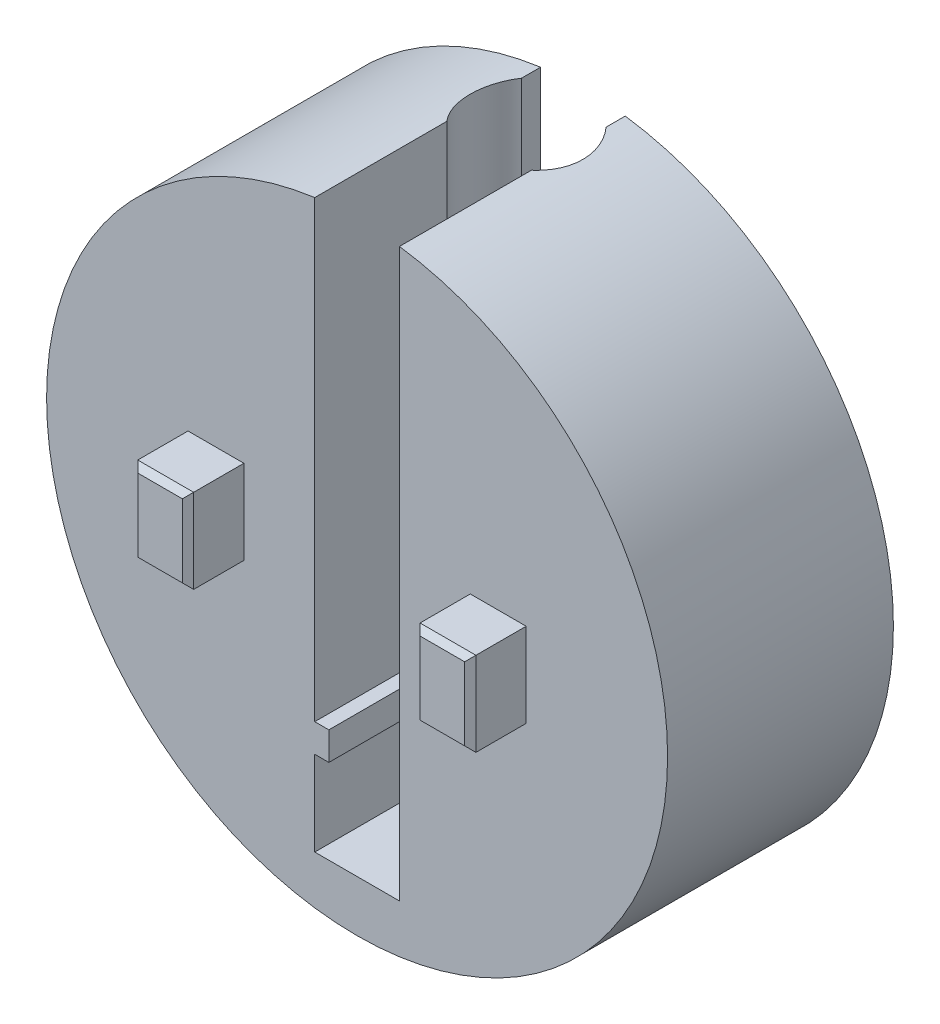
SolidWorks part; units mm, degrees
ref_plane "Front Plane" through (0, 0, 0) normal (0, 0, 1) x (1, 0, 0)
ref_plane "Top Plane" through (0, 0, 0) normal (0, 1, 0) x (1, 0, 0)
ref_plane "Right Plane" through (0, 0, 0) normal (1, 0, 0) x (0, 0, -1)
sketch "Sketch1" plane through (0, 0, 0) normal (0, 0, 1) x (1, 0, 0)
  line L0 (0, 0) -> (0, 11) construction
  line L1 (-1.5, 10.8972) -> (-1.5, -9.1833)
  line L2 (2, -5.1833) -> (-2, -5.1833)
  line L3 (2, -5.1833) -> (2, 10.8167)
  line L4 (2, 10.8167) -> (-2, 10.8167)
  line L5 (-2, -5.1833) -> (-2, 10.8167)
  line L6 (2, -5.1833) -> (-2, 10.8167) construction
  line L7 (2, 10.8167) -> (-2, -5.1833) construction
  line L8 (2, -5.1833) -> (-1, -5.1833)
  line L9 (2, -5.1833) -> (2, -6.1833)
  line L10 (2, -6.1833) -> (-1, -6.1833)
  line L11 (-1, -5.1833) -> (-1, -6.1833)
  line L12 (2, -6.1833) -> (-2, -6.1833)
  line L13 (2, -6.1833) -> (2, -9.1833)
  line L14 (2, -9.1833) -> (-2, -9.1833)
  line L15 (-2, -6.1833) -> (-2, -9.1833)
  line L16 (1.5, -9.1833) -> (1.5, 10.8972)
  circle A0 centre (0, 0) radius 11
  point P3 (0, 2.8167)
  dimension "D1" = 22
  dimension "D2" = 4
  dimension "D3" = 16
  dimension "D4" = 3
  dimension "D5" = 1
  dimension "D6" = 3
  dimension "D7" = 0.5
  dimension "D8" = 0.5
extrude "Boss-Extrude1" add sketch "Sketch1" along normal blind 8 contours L5 A0 L3 L9 L13 L14 L15 L12 L11 L2 | L12 L11 L2 L1 | L12 L15 L14 L1 | L5 L2 L1 L4 | L16 L2 L3 L4 | L16 L10 L9 L2 | L16 L14 L13 L10 | L4 A0 L16 | L1 A0 L4
sketch "Sketch8" plane through (0, 0, 0) normal (0, 1, 0) x (1, 0, 0)
  line L0 (-1.5, 0) -> (1.5, 0) construction
  line L1 (0, 0) -> (0, -2) construction
  circle A0 centre (0, -2) radius 2
  dimension "D1" = 4
sketch "Sketch4" plane through (0, 0, 0) normal (0, 0, -1) x (-1, 0, 0)
  line L0 (-2, 10.8167) -> (-2, -9.1833)
  line L1 (-2, -9.1833) -> (2, -9.1833)
  line L2 (2, -9.1833) -> (2, -6.1833)
  line L3 (2, -6.1833) -> (1, -6.1833)
  line L4 (1, -6.1833) -> (1, -5.1833)
  line L5 (1, -5.1833) -> (2, -5.1833)
  line L6 (2, -5.1833) -> (2, 10.8167)
  line L7 (-2, 10.8167) -> (2, 10.8167) construction
  line L8 (-1.5, 10.8972) -> (-1.5, -9.1833)
  line L9 (1.5, 10.8972) -> (1.5, -9.1833)
  circle A0 centre (0, 0) radius 11
  dimension "D1" = 22
  dimension "D2" = 0.5
  dimension "D3" = 0.5
  dimension "D4" = 20
  dimension "D5" = 4
  dimension "D6" = 0.5
extrude "pin hole" cut sketch "Sketch8" against normal up to surface (5.1833 mm away) and the other way through all up to face at (-1.25, -5.1833, 4)
sketch "Sketch6" plane through (0, 0, 0) normal (0, 0, -1) x (-1, 0, 0)
  line L0 (-11, 0) -> (11, 0) construction
  line L1 (-6, 1.5) -> (-4, -1.5) construction
  line L2 (-6, 1.5) -> (-4, 1.5)
  line L3 (-6, 1.5) -> (-6, -1.5)
  line L4 (-6, -1.5) -> (-4, -1.5)
  line L5 (-4, 1.5) -> (-4, -1.5)
  line L6 (4, 1.5) -> (6, 1.5)
  line L7 (4, 1.5) -> (4, -1.5)
  line L8 (4, -1.5) -> (6, -1.5)
  line L9 (6, 1.5) -> (6, -1.5)
  line L10 (4, 1.5) -> (6, -1.5) construction
  line L11 (-5, 0) -> (-11, 0) construction
  line L12 (5, 0) -> (11, 0) construction
  circle A1 centre (0, 0) radius 11 construction
  point P14 (-5, 0)
  point P15 (5, 0)
  dimension "D7" = 22
  dimension "D1" = 3
  dimension "D2" = 2
  dimension "D3" = 2
  dimension "D4" = 3
  dimension "D5" = 6
  dimension "D6" = 6
extrude "Cut-Extrude2" cut sketch "Sketch6" against normal blind 2 contours L5 L2 L3 L4 | L9 L6 L7 L8
sketch "Sketch7" plane through (0, 0, 8) normal (0, 0, 1) x (1, 0, 0)
  line L0 (-11, 0) -> (11, 0) construction
  line L1 (-5.99, 1.49) -> (-4.01, -1.49) construction
  line L2 (-5.99, 1.49) -> (-4.01, 1.49)
  line L3 (-5.99, 1.49) -> (-5.99, -1.49)
  line L4 (-5.99, -1.49) -> (-4.01, -1.49)
  line L5 (-4.01, 1.49) -> (-4.01, -1.49)
  line L6 (4.01, 1.49) -> (5.99, 1.49)
  line L7 (4.01, 1.49) -> (4.01, -1.49)
  line L8 (4.01, -1.49) -> (5.99, -1.49)
  line L9 (5.99, 1.49) -> (5.99, -1.49)
  line L10 (4.01, 1.49) -> (5.99, -1.49) construction
  line L11 (-5, 0) -> (-11, 0) construction
  line L12 (5, 0) -> (11, 0) construction
  arc A0 (-1.5, 10.8972) -> (1.5, 10.8972) centre (0, 0) ccw construction
  dimension "D1" = 1.98
  dimension "D2" = 2.98
  dimension "D3" = 1.98
  dimension "D4" = 2.98
  dimension "D5" = 6
  dimension "D6" = 6
extrude "Boss-Extrude4" add sketch "Sketch7" along normal blind 1.98
chamfer "Chamfer1" distance 0.2 angle 45 8 edges at (5, 1.49, 9.98) (5.99, 0, 9.98) (5, -1.49, 9.98) (4.01, 0, 9.98) (-5, 1.49, 9.98) (-4.01, 0, 9.98) (-5, -1.49, 9.98) (-5.99, 0, 9.98)
equation "\"ET_circle_diam\"= 0.3mm'add to diameter of outer circle"
